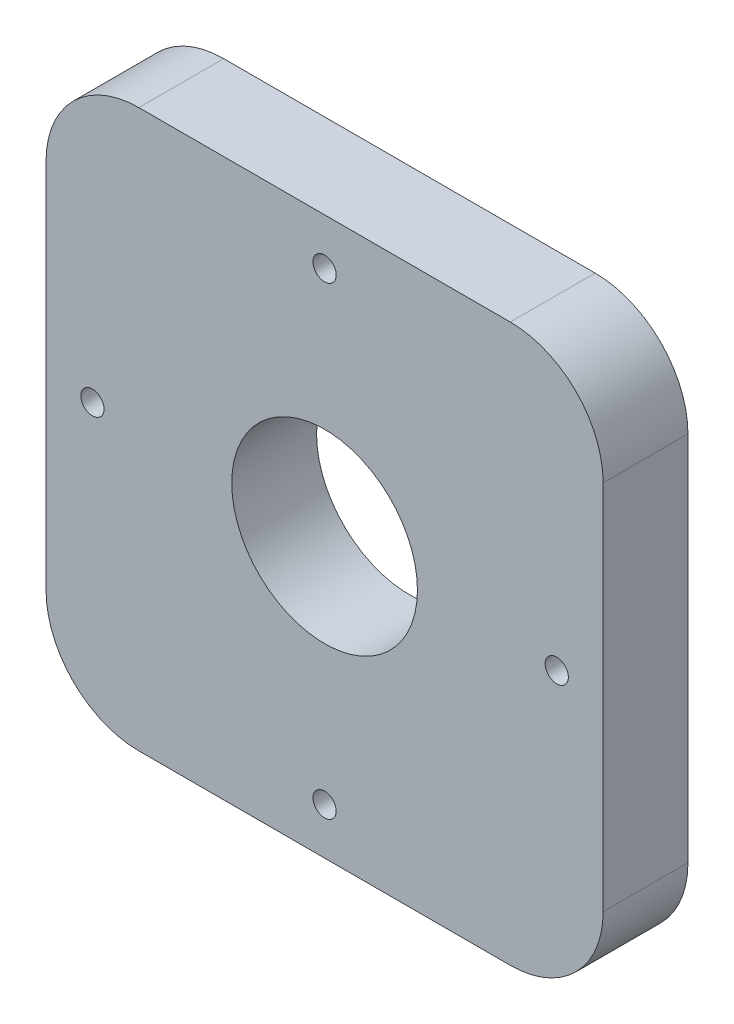
SolidWorks part; units mm, degrees
material "Acrylic (Medium-high impact)"
ref_plane "Front Plane" through (0, 0, 0) normal (0, 0, 1) x (1, 0, 0)
ref_plane "Top Plane" through (0, 0, 0) normal (0, 1, 0) x (1, 0, 0)
ref_plane "Right Plane" through (0, 0, 0) normal (1, 0, 0) x (0, 0, -1)
sketch "Sketch1" plane through (0, 0, 0) normal (0, 0, 1) x (1, 0, 0)
  line L0 (0, 0) -> (0, 19.05) construction
  line L1 (19.05, 19.05) -> (-19.05, 19.05)
  line L2 (0, 0) -> (-19.05, 19.05) construction
  line L3 (-19.05, 19.05) -> (-19.05, -19.05)
  line L4 (-19.05, 0) -> (0, 0) construction
  line L7 (19.05, 19.05) -> (19.05, -19.05)
  line L8 (19.05, -19.05) -> (-19.05, -19.05)
  point P18 (19.05, 0)
  dimension "D2" = 19.05
extrude "Boss-Extrude1" add sketch "Sketch1" along normal blind 5.8
sketch "Sketch2" plane through (0, 0, 5.8) normal (0, 0, 1) x (1, 0, 0)
  line L0 (19.05, 0) -> (-19.05, 0) construction
  line L1 (19.05, -19.05) -> (19.05, 19.05) construction
  line L2 (-19.05, 19.05) -> (-19.05, -19.05) construction
  line L3 (0, 0) -> (0, 15.875) construction
  line L5 (19.05, 19.05) -> (-19.05, 19.05) construction
  circle A0 centre (0, 15.875) radius 0.7937
  circle A1 centre (15.875, 0) radius 0.7937
  circle A2 centre (0, -15.875) radius 0.7938
  circle A3 centre (-15.875, 0) radius 0.7937
  dimension "D1" = 1.5875
  dimension "D2" = 3.175
  dimension "D3" = 4
extrude "Cut-Extrude1" cut sketch "Sketch2" against normal through all
sketch "Sketch3" plane through (0, 0, 5.8) normal (0, 0, 1) x (1, 0, 0)
  circle A0 centre (0, 0) radius 6.35
  dimension "D1" = 12.7
extrude "Cut-Extrude2" cut sketch "Sketch3" against normal blind 12.7
fillet "Fillet1" radius 6.35 4 edges at (19.05, -19.05, 2.9) (-19.05, -19.05, 2.9) (-19.05, 19.05, 2.9) (19.05, 19.05, 2.9)
other "Move Face1" [suppressed] parameters "D1"=0.2
